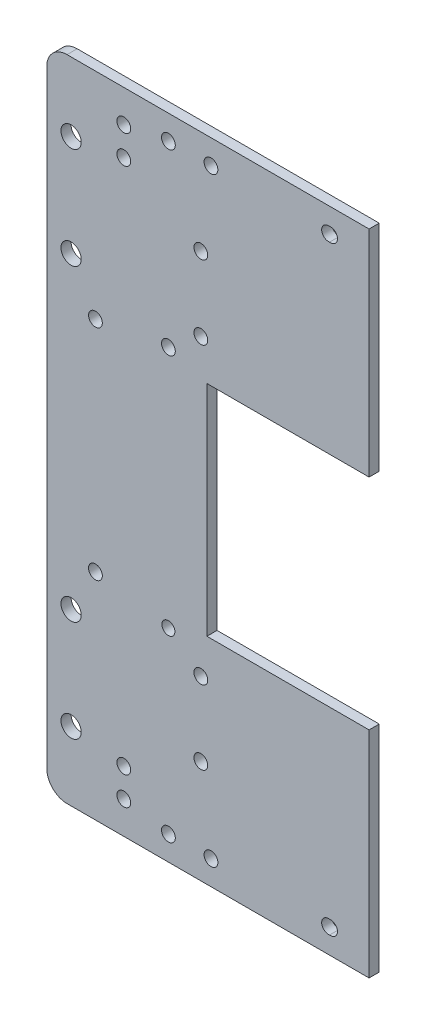
SolidWorks part; units mm, degrees
material "Hexcel AS4C (3000 丝)"
ref_plane "前视基准面" through (0, 0, 0) normal (0, 0, 1) x (1, 0, 0)
ref_plane "上视基准面" through (0, 0, 0) normal (0, 1, 0) x (1, 0, 0)
ref_plane "右视基准面" through (0, 0, 0) normal (1, 0, 0) x (0, 0, -1)
ref_plane "基准面4" through (0, 0, -50) normal (0, 0, -1) x (-1, 0, 0)
sketch "草图1" plane through (0, 0, -50) normal (0, 0, -1) x (-1, 0, 0)
  line L0 (-82, 0) -> (0, 0)
  line L1 (0, 0) -> (0, 160)
  line L2 (0, 160) -> (-82, 160)
  line L3 (-82, 160) -> (-82, 0)
extrude "凸台-拉伸1" add sketch "草图1" against normal blind 50
sketch "草图2" plane through (0, 160, 0) normal (0, 1, 0) x (-1, 0, 0)
  line L0 (0, -50) -> (0, -2.5)
  line L1 (0, -2.5) -> (-79.5, -2.5)
  line L2 (-79.5, -2.5) -> (-79.5, -50)
  line L3 (-79.5, -50) -> (0, -50)
extrude "切除-拉伸1" cut sketch "草图2" against normal through all
sketch "草图3" plane through (0, 0, -2.5) normal (0, 0, -1) x (-1, 0, 0)
  line L0 (-65, 89.5) -> (-20, 89.5)
  line L1 (-20, 94.5) -> (-65, 94.5)
  arc A0 (-65, 94.5) -> (-65, 89.5) centre (-65, 92) ccw
  arc A1 (-20, 89.5) -> (-20, 94.5) centre (-20, 92) ccw
extrude "切除-拉伸2" cut sketch "草图3" against normal through all
sketch "草图5" plane through (0, 0, -2.5) normal (0, 0, -1) x (-1, 0, 0)
  line L0 (-65, 65.5) -> (-20, 65.5)
  line L1 (-20, 70.5) -> (-65, 70.5)
  arc A0 (-65, 70.5) -> (-65, 65.5) centre (-65, 68) ccw
  arc A1 (-20, 65.5) -> (-20, 70.5) centre (-20, 68) ccw
extrude "切除-拉伸4" cut sketch "草图5" against normal through all
sketch "草图6" plane through (0, 0, -2.5) normal (0, 0, -1) x (-1, 0, 0)
  line L0 (-68, 50) -> (-38, 50)
  line L1 (-38, 53.2) -> (-68, 53.2)
  arc A0 (-68, 53.2) -> (-68, 50) centre (-68, 51.6) ccw
  arc A1 (-38, 50) -> (-38, 53.2) centre (-38, 51.6) ccw
extrude "切除-拉伸5" cut sketch "草图6" against normal through all
sketch "草图8" plane through (0, 0, -2.5) normal (0, 0, -1) x (-1, 0, 0)
  line L0 (-68, 106.8) -> (-38, 106.8)
  line L1 (-38, 110) -> (-68, 110)
  arc A0 (-68, 110) -> (-68, 106.8) centre (-68, 108.4) ccw
  arc A1 (-38, 106.8) -> (-38, 110) centre (-38, 108.4) ccw
extrude "切除-拉伸7" cut sketch "草图8" against normal through all
sketch "草图10" plane through (82, 0, 0) normal (1, 0, 0) x (0, 0, -1)
  line L0 (20.6906, 80) -> (16.6906, 86.9282)
  line L1 (16.6906, 73.0718) -> (20.6906, 80)
  arc A0 (16.6906, 86.9282) -> (16.6906, 73.0718) centre (23, 80) ccw
extrude "切除-拉伸9" cut sketch "草图10" against normal through all
sketch "草图11" plane through (82, 0, 0) normal (1, 0, 0) x (0, 0, -1)
  line L0 (24.1547, 89.2992) -> (24.1547, 82)
  line L1 (24.1547, 82) -> (32.1547, 82)
  arc A0 (32.1547, 82) -> (24.1547, 89.2992) centre (23, 80) ccw
extrude "切除-拉伸10" cut sketch "草图11" against normal through all
sketch "草图12" plane through (82, 0, 0) normal (1, 0, 0) x (0, 0, -1)
  line L0 (24.1547, 78) -> (24.1547, 70.7008)
  line L1 (32.1547, 78) -> (24.1547, 78)
  arc A0 (24.1547, 70.7008) -> (32.1547, 78) centre (23, 80) ccw
extrude "切除-拉伸11" cut sketch "草图12" against normal through all
sketch "草图13" plane through (82, 0, 0) normal (1, 0, 0) x (0, 0, -1)
  line L0 (36, 21.2) -> (14, 21.2)
  line L1 (14, 18) -> (36, 18)
  arc A0 (36, 18) -> (36, 21.2) centre (36, 19.6) ccw
  arc A1 (14, 21.2) -> (14, 18) centre (14, 19.6) ccw
extrude "切除-拉伸12" cut sketch "草图13" against normal through all
sketch "草图14" plane through (82, 0, 0) normal (1, 0, 0) x (0, 0, -1)
  line L0 (36, 31.2) -> (14, 31.2)
  line L1 (14, 28) -> (36, 28)
  arc A0 (36, 28) -> (36, 31.2) centre (36, 29.6) ccw
  arc A1 (14, 31.2) -> (14, 28) centre (14, 29.6) ccw
extrude "切除-拉伸13" cut sketch "草图14" against normal through all
sketch "草图15" plane through (82, 0, 0) normal (1, 0, 0) x (0, 0, -1)
  line L0 (36, 41.2) -> (14, 41.2)
  line L1 (14, 38) -> (36, 38)
  arc A0 (36, 38) -> (36, 41.2) centre (36, 39.6) ccw
  arc A1 (14, 41.2) -> (14, 38) centre (14, 39.6) ccw
extrude "切除-拉伸14" cut sketch "草图15" against normal through all
sketch "草图16" plane through (82, 0, 0) normal (1, 0, 0) x (0, 0, -1)
  line L0 (36, 51.2) -> (14, 51.2)
  line L1 (14, 48) -> (36, 48)
  arc A0 (36, 48) -> (36, 51.2) centre (36, 49.6) ccw
  arc A1 (14, 51.2) -> (14, 48) centre (14, 49.6) ccw
extrude "切除-拉伸15" cut sketch "草图16" against normal through all
sketch "草图17" plane through (82, 0, 0) normal (1, 0, 0) x (0, 0, -1)
  line L0 (36, 112) -> (14, 112)
  line L1 (14, 108.8) -> (36, 108.8)
  arc A0 (36, 108.8) -> (36, 112) centre (36, 110.4) ccw
  arc A1 (14, 112) -> (14, 108.8) centre (14, 110.4) ccw
extrude "切除-拉伸16" cut sketch "草图17" against normal through all
sketch "草图18" plane through (82, 0, 0) normal (1, 0, 0) x (0, 0, -1)
  line L0 (36, 122) -> (14, 122)
  line L1 (14, 118.8) -> (36, 118.8)
  arc A0 (36, 118.8) -> (36, 122) centre (36, 120.4) ccw
  arc A1 (14, 122) -> (14, 118.8) centre (14, 120.4) ccw
extrude "切除-拉伸17" cut sketch "草图18" against normal through all
sketch "草图19" plane through (82, 0, 0) normal (1, 0, 0) x (0, 0, -1)
  line L0 (36, 132) -> (14, 132)
  line L1 (14, 128.8) -> (36, 128.8)
  arc A0 (36, 128.8) -> (36, 132) centre (36, 130.4) ccw
  arc A1 (14, 132) -> (14, 128.8) centre (14, 130.4) ccw
extrude "切除-拉伸18" cut sketch "草图19" against normal through all
sketch "草图20" plane through (82, 0, 0) normal (1, 0, 0) x (0, 0, -1)
  line L0 (36, 142) -> (14, 142)
  line L1 (14, 138.8) -> (36, 138.8)
  arc A0 (36, 138.8) -> (36, 142) centre (36, 140.4) ccw
  arc A1 (14, 142) -> (14, 138.8) centre (14, 140.4) ccw
extrude "切除-拉伸19" cut sketch "草图20" against normal through all
draft "拔模1" type of draft neutral plane draft angle 30 faces to draft 1 face at (80.75, 85.6496, -24.1547) neutral plane through (0, 82, -24.1547) neutral plane normal (0, 1, 0) parameters "D1"=30
draft "拔模2" type of draft neutral plane draft angle 30 faces to draft 1 face at (80.75, 74.3504, -24.1547) neutral plane through (0, 78, -32.1547) neutral plane normal (0, -1, 0) parameters "D1"=30
hole_wizard "Ø3.2 (3.2) 直径孔1" positions "草图23" profile "草图22" hole size "Ø3.2" standard "ANSI Metric"
sketch "草图23" plane through (0, 0, 0) normal (0, 0, 1) x (1, 0, 0)
  point P0 (30, 32.75)
  point P1 (30, 38.75)
  point P2 (30, 50)
sketch "草图22" plane through (30, 32.75, 0) normal (1, 0, 0) x (0, -1, 0)
  line L0 (0, 0) -> (0, 50)
  line L1 (0, 50) -> (1.6, 50)
  line L2 (1.6, 50) -> (1.6, 0)
  line L5 (1.6, 0) -> (0, 0)
  line L11 (0, -6.35) -> (0, 107.95) construction
  dimension "通孔孔直径" = 3.2
  dimension "通孔孔深度" = 50
hole_wizard "Ø3.4 (3.4) 直径孔1" positions "草图25" profile "草图24" hole size "Ø3.4" standard "ANSI Metric"
sketch "草图25" plane through (0, 0, 0) normal (0, 0, 1) x (1, 0, 0)
  point P0 (30, 154)
  point P1 (40.5, 154)
  point P2 (69.5, 154)
  point P3 (69.5, 6)
  point P4 (40.5, 6)
  point P5 (30, 6)
  point P6 (30, 121.25)
  point P7 (30, 127.25)
  point P8 (30, 110)
  point P9 (19, 8)
  point P10 (19, 15)
  point P11 (19, 145)
  point P12 (12, 53)
  point P13 (12, 107)
  point P14 (19, 152)
  point P15 (22, 124.25)
  point P16 (22, 35.75)
sketch "草图24" plane through (30, 154, 0) normal (1, 0, 0) x (0, -1, 0)
  line L0 (0, 0) -> (0, 50)
  line L1 (0, 50) -> (1.7, 50)
  line L2 (1.7, 50) -> (1.7, 0)
  line L5 (1.7, 0) -> (0, 0)
  line L11 (0, -6.35) -> (0, 107.95) construction
  dimension "通孔孔直径" = 3.4
  dimension "通孔孔深度" = 50
hole_wizard "Ø3.2 (3.2) 直径孔2" positions "草图27" profile "草图26" hole size "Ø3.2" standard "ANSI Metric"
sketch "草图27" plane through (82, 0, 0) normal (1, 0, 0) x (0, 0, -1)
  point P0 (9.5, 150)
  point P1 (17.5, 150)
  point P2 (25.5, 150)
  point P3 (33.5, 150)
  point P4 (41.5, 150)
  point P5 (41.5, 10)
  point P6 (33.5, 10)
  point P7 (25.5, 10)
  point P8 (17.5, 10)
  point P9 (10.5, 90)
  point P10 (23, 100)
  point P11 (35.5, 90)
  point P12 (9.5, 10)
  point P13 (35.5, 70)
  point P14 (23, 60)
  point P15 (10.5, 70)
sketch "草图26" plane through (82, 150, -9.5) normal (0, 1, 0) x (0, 0, -1)
  line L0 (0, 0) -> (0, 82)
  line L1 (0, 82) -> (1.6, 82)
  line L2 (1.6, 82) -> (1.6, 0)
  line L5 (1.6, 0) -> (0, 0)
  line L11 (0, -6.35) -> (0, 107.95) construction
  dimension "通孔孔直径" = 3.2
  dimension "通孔孔深度" = 82
hole_wizard "Ø5.0 (5) 直径孔1" positions "草图29" profile "草图28" hole size "Ø5.0" standard "ANSI Metric"
sketch "草图29" plane through (0, 0, 0) normal (0, 0, 1) x (1, 0, 0)
  point P0 (6, 17)
  point P1 (6, 42)
  point P2 (6, 118)
  point P3 (6, 143)
sketch "草图28" plane through (6, 17, 0) normal (1, 0, 0) x (0, -1, 0)
  line L0 (0, 0) -> (0, 50)
  line L1 (0, 50) -> (2.5, 50)
  line L2 (2.5, 50) -> (2.5, 0)
  line L5 (2.5, 0) -> (0, 0)
  line L11 (0, -6.35) -> (0, 107.95) construction
  dimension "通孔孔直径" = 5
  dimension "通孔孔深度" = 50
fillet "圆角3" radius 5 4 edges at (80.75, 160, -50) (80.75, 0, -50) (0, 160, -1.25) (0, 0, -1.25)
ref_plane "基准面6" through (79.5, 0, 0) normal (-1, 0, 0) x (0, 0, 1)
sketch "草图31" plane through (79.5, 0, 0) normal (-1, 0, 0) x (0, 0, 1)
  line L0 (-2.5, 0) -> (0, 0)
  line L5 (-2.5, 160) -> (-2.5, 0)
  line L7 (-2.5, 160) -> (0, 160)
  line L8 (0, 160) -> (0, 0)
extrude "切除-拉伸21" cut sketch "草图31" against normal blind 10
sketch "草图32" plane through (0, 0, 0) normal (0, 0, 1) x (1, 0, 0)
  line L0 (79.5, 55) -> (79.5, -55) construction
  circle A0 centre (38, 25.5) radius 1.7
  circle A1 centre (38, 43.7) radius 1.7
  dimension "D4" = 3.4
  dimension "D5" = 3.4
  dimension "D1" = 41.5
  dimension "D2" = 41.5
extrude "切除-拉伸22" cut sketch "草图32" against normal blind 10
sketch "草图33" plane through (0, 0, 0) normal (0, 0, 1) x (1, 0, 0)
  line L0 (79.5, 0) -> (79.5, 160) construction
  circle A0 centre (38, 134.5) radius 1.7
  circle A1 centre (38, 116.3) radius 1.7
  dimension "D4" = 3.4
  dimension "D5" = 3.4
  dimension "D1" = 41.5
  dimension "D3" = 18.2
extrude "切除-拉伸23" cut sketch "草图33" against normal blind 10
sketch "草图34" plane through (0, 0, 0) normal (0, 0, 1) x (1, 0, 0)
  line L1 (13.855, 98.1046) -> (74.4514, 98.1046)
  line L2 (13.855, 98.1046) -> (13.855, 60.3629)
  line L3 (13.855, 60.3629) -> (74.4514, 60.3629)
  line L4 (74.4514, 98.1046) -> (74.4514, 60.3629)
  line L5 (34.6129, 111.5239) -> (70.4676, 111.5239)
  line L6 (34.6129, 111.5239) -> (34.6129, 105.2336)
  line L7 (34.6129, 105.2336) -> (70.4676, 105.2336)
  line L8 (70.4676, 111.5239) -> (70.4676, 105.2336)
  line L9 (34.6129, 54.9113) -> (72.5644, 54.9113)
  line L10 (34.6129, 54.9113) -> (34.6129, 47.1533)
  line L11 (34.6129, 47.1533) -> (72.5644, 47.1533)
  line L12 (72.5644, 54.9113) -> (72.5644, 47.1533)
  line L13 (17.4195, 40.4436) -> (34.6129, 40.4436)
  line L14 (17.4195, 40.4436) -> (17.4195, 29.7501)
  line L15 (17.4195, 29.7501) -> (34.6129, 29.7501)
  line L16 (34.6129, 40.4436) -> (34.6129, 29.7501)
  line L17 (19.3066, 129.9754) -> (34.6129, 129.9754)
  line L18 (19.3066, 129.9754) -> (19.3066, 116.9755)
  line L19 (19.3066, 116.9755) -> (34.6129, 116.9755)
  line L20 (34.6129, 129.9754) -> (34.6129, 116.9755)
extrude "凸台-拉伸2" add sketch "草图34" against normal up to surface (2.5 mm away) up to face at (39.7, 134.5, -2.5)
sketch "草图35" plane through (0, 0, 0) normal (0, 0, 1) x (1, 0, 0)
  line L0 (79.5, 80) -> (-20.0133, 80) construction
  line L1 (79.5, 0) -> (79.5, 160) construction
  line L2 (79.5, 80) -> (79.5, 107)
  line L3 (79.5, 107) -> (39.5, 107)
  line L4 (39.5, 107) -> (39.5, 53)
  line L5 (39.5, 80) -> (79.5, 80)
  line L6 (79.5, 80) -> (79.5, 107)
  line L7 (79.5, 53) -> (39.5, 53)
  line L8 (79.5, 80) -> (79.5, 64.1878)
  line L9 (79.5, 55) -> (79.5, -55) construction
  line L10 (79.5, 107) -> (79.5, 53)
  dimension "D1" = 40
extrude "切除-拉伸24" cut sketch "草图35" against normal through all contours L10 L8 L5 L4 L7 | L4 L5 L2 L3
sketch "草图37" plane through (0, 0, 0) normal (0, 0, 1) x (1, 0, 0)
  circle A0 centre (70, 6) radius 1.7
  circle A1 centre (70, 154) radius 1.7
extrude "切除-拉伸25" cut sketch "草图37" against normal blind 10
